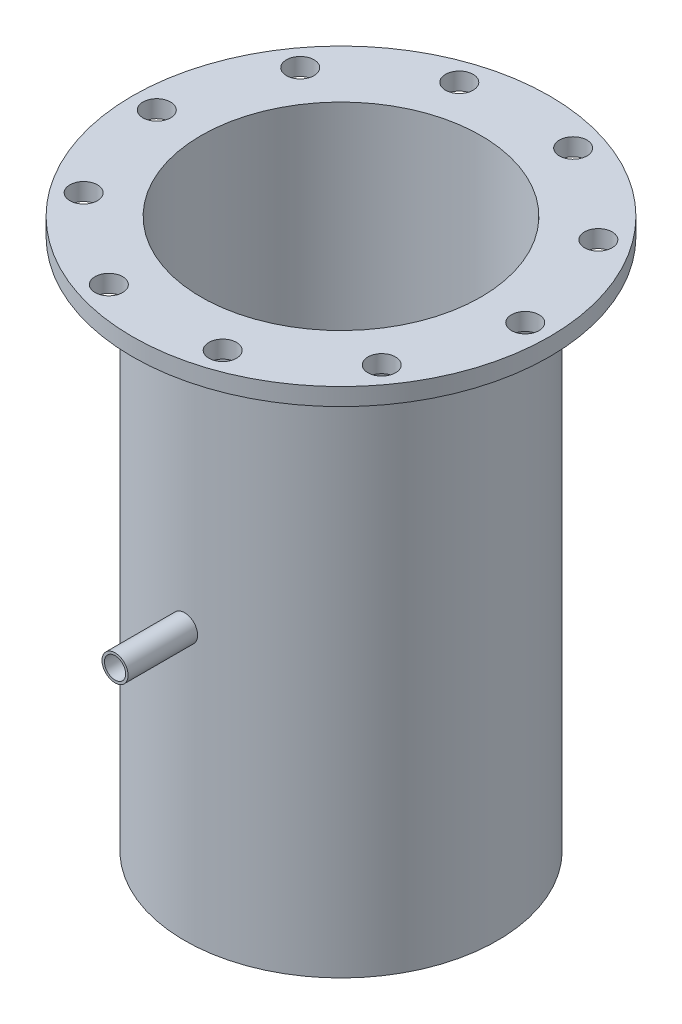
SolidWorks part; units mm, degrees
other "DetailItem1"
other "DetailItem2"
other "Weld Folder"
other "Weld Bead1"
other "Weld Bead2"
material "1023 Carbon Steel Sheet (SS)"
ref_plane "Front Plane" through (0, 0, 0) normal (0, 0, 1) x (1, 0, 0)
ref_plane "Top Plane" through (0, 0, 0) normal (0, 1, 0) x (1, 0, 0)
ref_plane "Right Plane" through (0, 0, 0) normal (1, 0, 0) x (0, 0, -1)
sketch "Sketch1" plane through (0, 0, 0) normal (0, 0, 1) x (1, 0, 0)
  line L0 (0, 0) -> (0, -134.8652) construction
  line L1 (51.1302, 0) -> (51.1302, -188.027)
  line L2 (51.1302, -200.6) -> (57.15, -200.6)
  line L3 (57.15, -200.6) -> (57.15, -8.89)
  line L4 (54.61, -6.35) -> (76.2, -6.35)
  line L5 (76.2, -6.35) -> (76.2, 0)
  line L6 (76.2, 0) -> (51.1302, 0)
  line L7 (51.1302, -188.027) -> (53.848, -188.027)
  line L8 (53.848, -188.027) -> (53.848, -191.075)
  line L9 (53.848, -191.075) -> (51.1302, -191.075)
  line L11 (51.1302, -191.075) -> (51.1302, -200.6)
  line L12 (57.15, -8.89) -> (54.61, -6.35)
  line L15 (-56.1848, -191.075) -> (56.1848, -191.075) construction
  line L16 (-50.1022, -191.075) -> (50.1022, -191.075) construction
  dimension "D1" = 51.1302
  dimension "D2" = 57.15
  dimension "D3" = 76.2
  dimension "D4" = 6.35
  dimension "D5" = 9.525
  dimension "D6" = 53.848
  dimension "D7" = 3.048
  dimension "D9" = 45
  dimension "D10" = 2.54
revolve "Revolve1" add sketch "Sketch1" angle 360 about L0
hole_wizard "Tap Drill for 3/8-16 Tap1" positions "Sketch2" profile "Sketch3" hole size "3/8" standard "ANSI Inch" end condition through all
sketch "Sketch2" plane through (0, 0, 0) normal (0, 1, 0) x (1, 0, 0)
  point P1 (67.31, 0)
  dimension "D1" = 67.31
sketch "Sketch3" plane through (67.31, 0, 0) normal (1, 0, 0) x (0, 0, 1)
  line L0 (0, 0) -> (0, 200.6)
  line L1 (0, 200.6) -> (5.0419, 200.6)
  line L2 (5.0419, 200.6) -> (5.0419, 0)
  line L5 (5.0419, 0) -> (0, 0)
  line L11 (0, -6.35) -> (0, 107.95) construction
  dimension "Thru Hole Dia." = 10.0838
  dimension "Thru Hole Depth" = 200.6
pattern_circular "CirPattern1" count 10 over 360 about axis through (0, 0, 0) along (0, 1, 0) of "Tap Drill for 3/8-16 Tap1"
ref_plane "Plane1" through (0, 0, 57.15) normal (0, 0, 1) x (1, 0, 0)
sketch "Sketch4" plane through (0, 0, 57.15) normal (0, 0, 1) x (1, 0, 0)
  circle A0 centre (0, -101.6) radius 4.7625
  circle A1 centre (0, -101.6) radius 3.8735
  dimension "D1" = 9.525
  dimension "D2" = 0.889
  dimension "D3" = 101.6
extrude "Boss-Extrude1" add sketch "Sketch4" along normal blind 25.4 separate body
hole_wizard "1/8 (0.125) Diameter Hole3" positions "3DSketch2" profile "Sketch11" hole size "1/8" standard "ANSI Inch"
sketch3d "3DSketch2"
  circle A0 centre (0, -101.6, 57.15) radius 4.1349 construction
  circle A1 centre (0, -101.6, 57.15) radius 4.7625 construction
  point P6 (0, -101.6, 61.2849)
  point P19 (0, -101.6, 61.9125)
  point P21 (0, -101.6, 57.15)
sketch "Sketch11" plane through (0, -101.6, 57.15) normal (1, 0, 0) x (0, -1, 0)
  line L0 (0, 0) -> (0, 26.3539)
  line L1 (0, 26.3539) -> (1.5875, 25.4)
  line L2 (1.5875, 25.4) -> (1.5875, 0)
  line L5 (1.5875, 0) -> (0, 0)
  line L10 (0, 26.3539) -> (-1.5875, 25.4) construction
  line L11 (0, -6.35) -> (0, 107.95) construction
  dimension "Hole Dia." = 3.175
  dimension "Hole Depth" = 25.4
  dimension "Drill Angle" = 118
